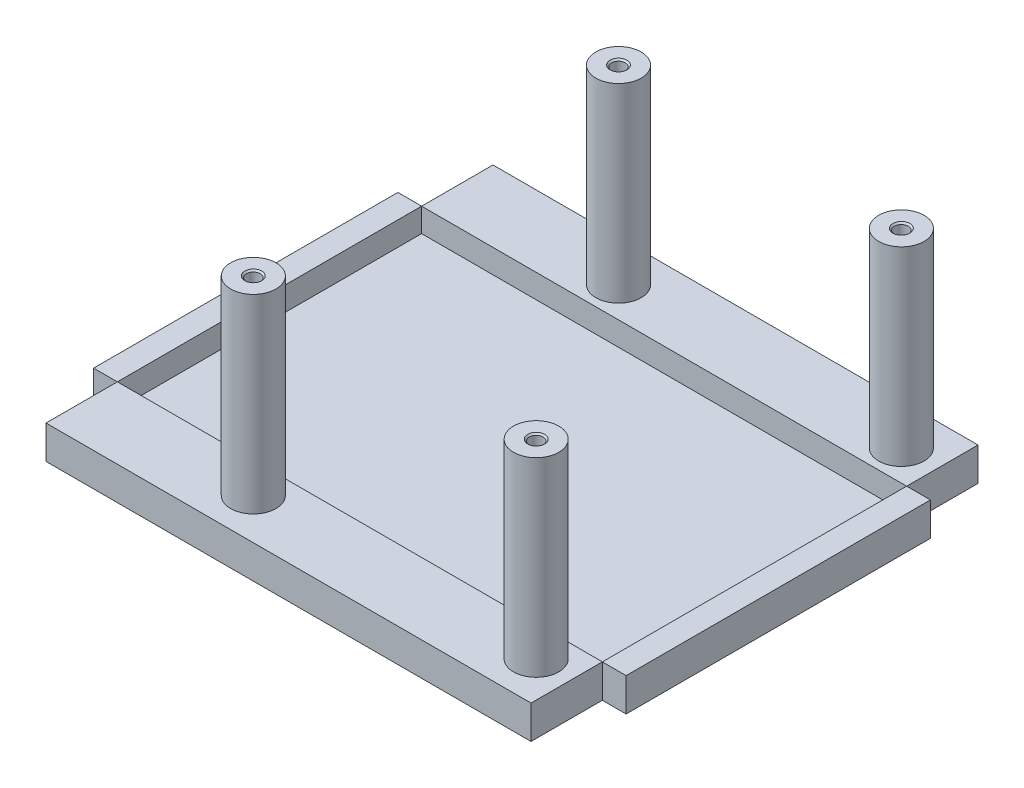
SolidWorks part; units mm, degrees
ref_plane "前视基准面" through (0, 0, 0) normal (0, 0, 1) x (1, 0, 0)
ref_plane "上视基准面" through (0, 0, 0) normal (0, 1, 0) x (1, 0, 0)
ref_plane "右视基准面" through (0, 0, 0) normal (1, 0, 0) x (0, 0, -1)
other "Configuration Table"
sketch "草图1" plane through (0, 0, 0) normal (0, 1, 0) x (1, 0, 0)
  line L0 (0, 64) -> (0, 79)
  line L1 (0, 0) -> (102, 0)
  line L2 (0, 0) -> (0, 64)
  line L3 (0, 64) -> (102, 64)
  line L4 (102, 0) -> (102, 64)
  line L5 (0, 0) -> (0, -15)
  line L6 (0, 79) -> (102, 79)
  line L7 (102, 79) -> (102, 64)
  line L8 (102, 0) -> (102, -15)
  line L9 (102, -15) -> (0, -15)
  line L11 (0, 64) -> (-5, 64)
  line L12 (0, 64) -> (0, 0)
  line L13 (0, 0) -> (-5, 0)
  line L14 (-5, 64) -> (-5, 0)
  line L15 (102, 64) -> (107, 64)
  line L16 (102, 64) -> (102, 0)
  line L17 (102, 0) -> (107, 0)
  line L18 (107, 64) -> (107, 0)
  dimension "D1" = 64
  dimension "D2" = 102
  dimension "D3" = 15
  dimension "D4" = 15
  dimension "D5" = 5
  dimension "D6" = 5
extrude "凸台-拉伸7" add sketch "草图1" along normal blind 7 contours L11 L14 L13 L2 | L7 L6 L0 L3 | L18 L15 L4 L17 | L9 L8 L1 L5
sketch "草图3" plane through (0, 7, 0) normal (0, 1, 0) x (1, 0, 0)
  line L5 (102, 63.99) -> (102, 0.01)
  line L6 (102, 0.01) -> (0, 0.01)
  line L7 (0, 0.01) -> (0, 63.99)
  line L8 (0, 63.99) -> (102, 63.99)
  dimension "D1" = 63.98
  dimension "D2" = 0.01
extrude "切除-拉伸5" cut sketch "草图3" against normal blind 5
sketch "草图11" plane through (0, 7, 0) normal (0, 1, 0) x (1, 0, 0)
  line L0 (35, 70.4) -> (102, 70.4) construction
  line L1 (0, 64) -> (0, 79) construction
  line L2 (102, 79) -> (102, 64) construction
  line L3 (0, 79) -> (0, 70.5) construction
  line L5 (-5, 32) -> (107, 32) construction
  line L6 (-5, 64) -> (-5, 0) construction
  line L7 (107, 64) -> (107, 0) construction
  line L8 (0, 79) -> (102, 79) construction
  circle A0 centre (35, 70.4) radius 4.77
  circle A1 centre (94.4848, 70.4) radius 4.77
  circle A2 centre (94.4848, -6.4) radius 4.77
  circle A3 centre (35, -6.4) radius 4.77
  point P20 (94.4848, 70.4)
  dimension "D1" = 8.6
  dimension "D2" = 9.54
  dimension "D4" = 9.54
  dimension "D3" = 35
extrude "凸台-拉伸8" add sketch "草图11" along normal blind 40
hole_wizard "M3.5 螺纹孔2" positions "3D草图2" profile "草图13" tap size "M3.5" standard "GB"
sketch3d "3D草图2"
  line L0 (35, 47, -70.4) -> (35, 7, -70.4) construction
  line L1 (94.4848, 47, -70.4) -> (94.4848, 7, -70.4) construction
  line L2 (94.4848, 47, 6.4) -> (94.4848, 7, 6.4) construction
  line L3 (35, 47, 6.4) -> (35, 7, 6.4) construction
  point P0 (35, 47, -70.4)
  point P4 (94.4848, 47, -70.4)
  point P8 (94.4848, 47, 6.4)
  point P12 (35, 47, 6.4)
sketch "草图13" plane through (35, 47, -70.4) normal (1, 0, 0) x (0, 0, 1)
  line L0 (0, 0) -> (0, 10.8712)
  line L1 (0, 10.8712) -> (1.45, 10)
  line L2 (1.45, 10) -> (1.45, 0.325)
  line L3 (1.45, 0.325) -> (1.775, 0)
  line L5 (1.775, 0) -> (0, 0)
  line L6 (-1.45, 0.325) -> (-1.775, 0) construction
  line L10 (0, 10.8712) -> (-1.45, 10) construction
  line L11 (0, -6.35) -> (0, 107.95) construction
  dimension "螺纹孔钻头直径" = 2.9
  dimension "螺纹孔钻头深度" = 10
  dimension "近端锥形沉头孔直径" = 3.55
  dimension "近端锥形沉头孔角度" = 90
  dimension "导头角度" = 118
cosmetic thread "孔螺蚊线5" parameters "D1"=19, "D2"=3.5
cosmetic thread "孔螺蚊线6" parameters "D1"=19, "D2"=3.5
cosmetic thread "孔螺蚊线7" parameters "D1"=19, "D2"=3.5
cosmetic thread "孔螺蚊线8" parameters "D1"=19, "D2"=3.5
